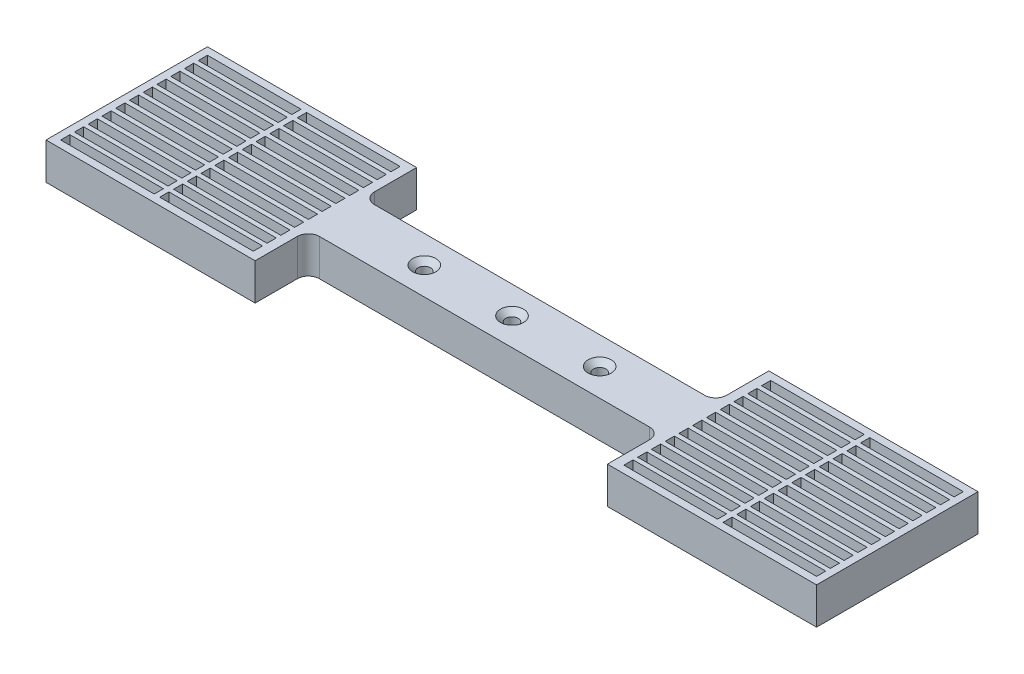
SolidWorks part; units mm, degrees
ref_plane "Front Plane" through (0, 0, 0) normal (0, 0, 1) x (1, 0, 0)
ref_plane "Top Plane" through (0, 0, 0) normal (0, 1, 0) x (1, 0, 0)
ref_plane "Right Plane" through (0, 0, 0) normal (1, 0, 0) x (0, 0, -1)
sketch "Sketch1" plane through (0, 0, 0) normal (0, 1, 0) x (1, 0, 0)
  line L0 (-105, 0) -> (105, 0) construction
  line L1 (-105, -22) -> (-48, -22)
  line L2 (-105, -22) -> (-105, 22)
  line L3 (-105, 22) -> (-48, 22)
  line L4 (105, -22) -> (105, 22)
  line L5 (48, 22) -> (48, 7.5)
  line L7 (0, 7.5) -> (0, -7.5) construction
  line L8 (48, 7.5) -> (-48, 7.5)
  line L11 (-48, 22) -> (-48, 7.5)
  line L12 (-48, -22) -> (-48, -7.5)
  line L13 (48, -7.5) -> (-48, -7.5)
  line L14 (48, -22) -> (48, -7.5)
  line L15 (48, 22) -> (105, 22)
  line L16 (48, -22) -> (105, -22)
  point P0 (0, 0)
  point P8 (23.9, 0)
  point P12 (-23.9, 0)
  point P14 (0, 7.5)
  point P21 (0, -7.5)
  dimension "D1" = 210
  dimension "D2" = 44
  dimension "D3" = 23.9
  dimension "D4" = 57
  dimension "D5" = 15
extrude "Boss-Extrude1" add sketch "Sketch1" against normal blind 10
sketch "Sketch2" plane through (0, 0, 0) normal (0, 1, 0) x (1, 0, 0)
  line L0 (-105, 0) -> (105, 0) construction
  line L1 (-105, 22) -> (-105, -22) construction
  line L2 (105, -22) -> (105, 22) construction
  line L3 (105, -22) -> (105, 22) construction
  line L4 (77.5, -1.25) -> (103, -1.25)
  line L5 (77.5, -1.25) -> (77.5, 1.25)
  line L6 (77.5, 1.25) -> (103, 1.25)
  line L7 (103, -1.25) -> (103, 1.25)
  line L8 (77.5, -1.25) -> (103, 1.25) construction
  line L9 (77.5, 1.25) -> (103, -1.25) construction
  point P6 (90.25, 0)
  dimension "D1" = 25.5
  dimension "D2" = 2.5
  dimension "D3" = 2
extrude "Cut-Extrude1" cut sketch "Sketch2" against normal up to next
pattern_linear "LPattern1" count 6 spacing 3.75 along (0, 0, -1) count 6 spacing 3.75 along (0, 0, 1) of "Cut-Extrude1"
pattern_linear "LPattern2" count 2 spacing 27 along (-1, 0, 0) of "LPattern1", "Cut-Extrude1"
hole_wizard "CSK for M3 Flat Head Machine Screw1" positions "3DSketch3" profile "Sketch5" countersink size "M3" standard "ANSI Metric" end condition up to next
sketch3d "3DSketch3"
  point P0 (23.9, 0, 0)
  point P2 (-23.9, 0, 0)
  point P9 (0, 0, 0)
sketch "Sketch5" plane through (23.9, 0, 0) normal (1, 0, 0) x (0, 0, 1)
  line L0 (0, 0) -> (0, 10)
  line L1 (0, 10) -> (1.7, 10)
  line L2 (1.7, 10) -> (1.7, 1.45)
  line L3 (1.7, 1.45) -> (3.15, 0)
  line L5 (3.15, 0) -> (0, 0)
  line L6 (-1.7, 1.45) -> (-3.15, 0) construction
  line L11 (0, -6.35) -> (0, 107.95) construction
  dimension "Thru Hole Dia." = 3.4
  dimension "Thru Hole Depth" = 10
  dimension "Near C'Sink Dia." = 6.3
  dimension "Near C'Sink Angle" = 90
ref_plane "Plane1" through (0, 0, 0) normal (1, 0, 0) x (0, 0, -1)
mirror "Mirror1" about plane through (0, 0, 0) normal (1, 0, 0) of "LPattern2", "Cut-Extrude1", "LPattern1"
fillet "Fillet1" radius 3 4 edges at (-48, -5, -7.5) (-48, -5, 7.5) (48, -5, 7.5) (48, -5, -7.5)
